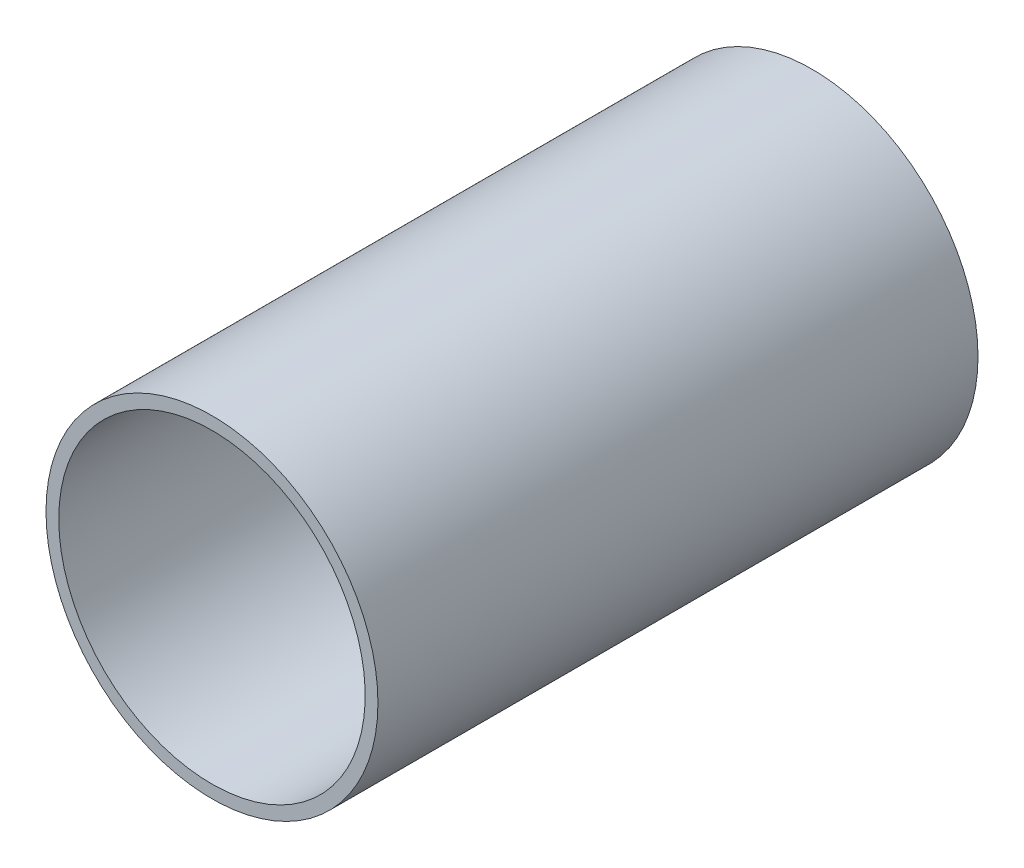
SolidWorks part; units mm, degrees
material "PMMA"
ref_plane "Plan de face" through (0, 0, 0) normal (0, 0, 1) x (1, 0, 0)
ref_plane "Plan de dessus" through (0, 0, 0) normal (0, 1, 0) x (1, 0, 0)
ref_plane "Plan de droite" through (0, 0, 0) normal (1, 0, 0) x (0, 0, -1)
ref_plane "Plan1" through (0, 0, 0) normal (0, -1, 0) x (1, 0, 0)
sketch "Esquisse1" plane through (0, 0, 0) normal (0, -1, 0) x (1, 0, 0)
  line L0 (82.55, -149.225) -> (82.55, 149.225)
  line L1 (82.55, 149.225) -> (76.2, 149.225)
  line L2 (76.2, 149.225) -> (76.2, -149.225)
  line L3 (76.2, -149.225) -> (82.55, -149.225)
  line L4 (0, 149.225) -> (0, -149.225) construction
revolve "Révolution1" add sketch "Esquisse1" angle 360 about L4
